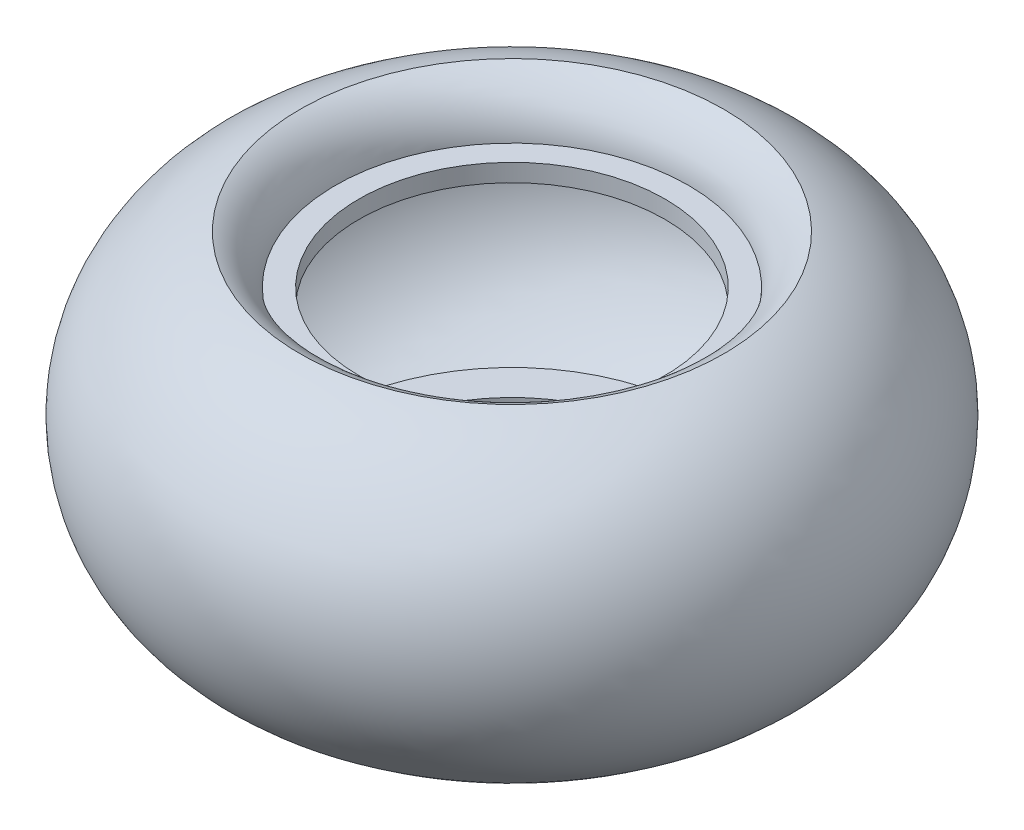
SolidWorks part; units mm, degrees
ref_plane "Front Plane" through (0, 0, 0) normal (0, 0, 1) x (1, 0, 0)
ref_plane "Top Plane" through (0, 0, 0) normal (0, 1, 0) x (1, 0, 0)
ref_plane "Right Plane" through (0, 0, 0) normal (1, 0, 0) x (0, 0, -1)
sketch "Sketch1" plane through (0, 0, 0) normal (0, 0, 1) x (1, 0, 0)
  line L0 (0, 0) -> (0, 44.7758) construction
  line L1 (0, 0) -> (41.8299, 0) construction
  line L2 (15, 9.4) -> (16.1181, 7.9) construction
  line L3 (15, -9.4) -> (16.1181, -7.9) construction
  line L4 (15, 9.4) -> (13, 9.4)
  line L5 (13, 9.4) -> (13, 7.9)
  line L6 (13, 7.9) -> (16.1181, 7.9)
  line L7 (16.1181, -7.9) -> (13, -7.9)
  line L8 (13, -7.9) -> (13, -9.4)
  line L9 (13, -9.4) -> (15, -9.4)
  line L10 (28, 12.8407) -> (28, -9.7767) construction
  line L11 (16.7795, 13.5) -> (18, 13.5) construction
  line L12 (16.1181, 7.9) -> (17.9621, 11.4066)
  line L13 (16.1181, -7.9) -> (17.9621, -11.4066)
  arc A2 (18, 13.5) -> (18, -13.5) centre (13.8875, 0) cw
  arc A3 (18, 13.5) -> (15, 9.4) centre (19.9756, 8.9069) ccw
  arc A4 (18, -13.5) -> (15, -9.4) centre (19.9756, -8.9069) cw
  arc A6 (17.9621, 11.4066) -> (17.9621, -11.4066) centre (13.8875, 0) cw
  point P23 (0, 0)
  dimension "D2" = 1.5
  dimension "D4" = 10
  dimension "D5" = 13.5
  dimension "D8" = 28
  dimension "D9" = 2
  dimension "D10" = 5
  dimension "D1" = 28
  dimension "D3" = 2
  dimension "D6" = 13
  dimension "D7" = 5.6
  dimension "D11" = 7.9
revolve "Revolve1" add sketch "Sketch1" angle 360 about L0
